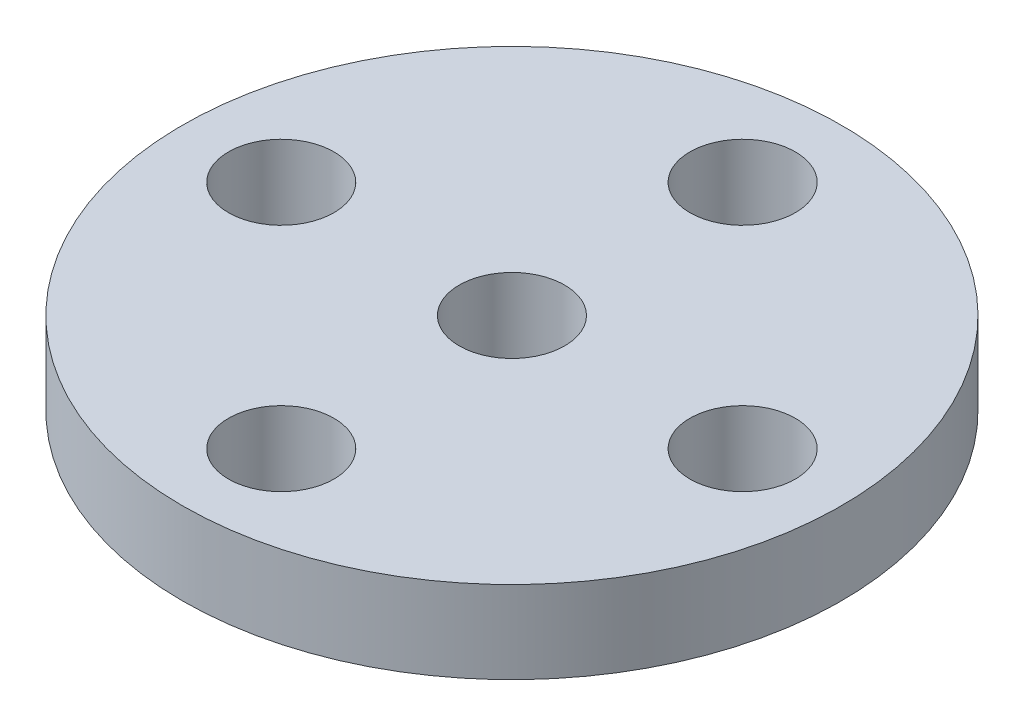
SolidWorks part; units mm, degrees
ref_plane "前视基准面" through (0, 0, 0) normal (0, 0, 1) x (1, 0, 0)
ref_plane "上视基准面" through (0, 0, 0) normal (0, 1, 0) x (1, 0, 0)
ref_plane "右视基准面" through (0, 0, 0) normal (1, 0, 0) x (0, 0, -1)
sketch "草图1" plane through (0, 0, 0) normal (0, 1, 0) x (1, 0, 0)
  circle A0 centre (0, 0) radius 4
  dimension "D1" = 8
extrude "凸台-拉伸1" add sketch "草图1" along normal blind 2
sketch "草图2" plane through (0, 2, 0) normal (0, 1, 0) x (1, 0, 0)
  circle A0 centre (0, 0) radius 10
  dimension "D1" = 20
extrude "凸台-拉伸2" add sketch "草图2" along normal blind 2.5
sketch "草图3" plane through (0, 4.5, 0) normal (0, 1, 0) x (1, 0, 0)
  circle A0 centre (0, 0) radius 1.6
  circle A1 centre (0, 7) radius 1.6
  circle A2 centre (7, 0) radius 1.6
  circle A3 centre (0, -7) radius 1.6
  circle A4 centre (-7, 0) radius 1.6
  point P14 (0, 0)
  dimension "D1" = 3.2
  dimension "D3" = 14
  dimension "D2" = 4
extrude "切除-拉伸1" cut sketch "草图3" against normal through all
